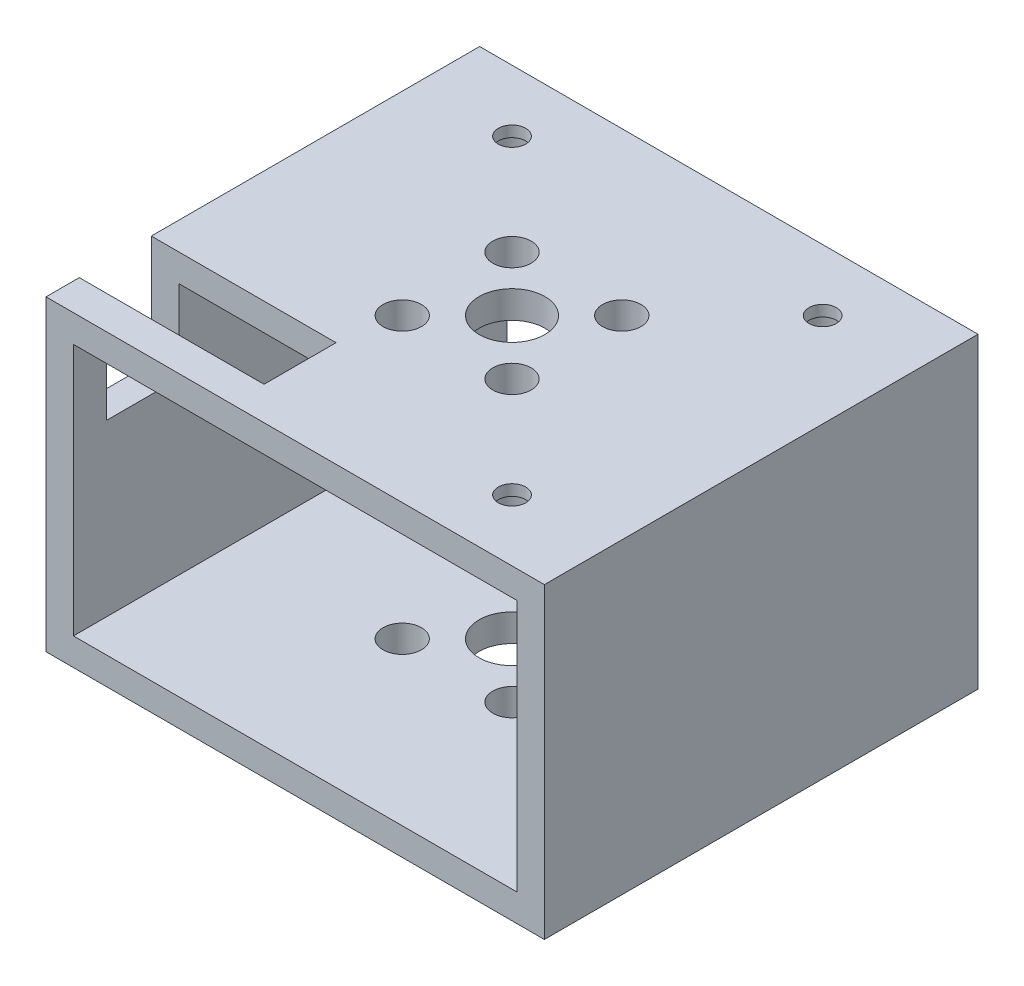
SolidWorks part; units mm, degrees
ref_plane "前视基准面" through (0, 0, 0) normal (0, 0, 1) x (1, 0, 0)
ref_plane "上视基准面" through (0, 0, 0) normal (0, 1, 0) x (1, 0, 0)
ref_plane "右视基准面" through (0, 0, 0) normal (1, 0, 0) x (0, 0, -1)
other "Configuration Table"
sketch "草图1" plane through (0, 0, 0) normal (0, 1, 0) x (1, 0, 0)
  line L0 (-20, 9.75) -> (-25, 9.75) construction
  line L1 (-20, 19.75) -> (20, 19.75) construction
  line L2 (-20, 19.75) -> (-20, -19.75) construction
  line L3 (-20, -19.75) -> (20, -19.75) construction
  line L4 (20, 19.75) -> (20, -19.75) construction
  line L5 (-20, 19.75) -> (20, -19.75) construction
  line L6 (-20, -19.75) -> (20, 19.75) construction
  line L7 (-25, 19.75) -> (25, 19.75)
  line L8 (-25, 19.75) -> (-25, -19.75)
  line L9 (-25, -19.75) -> (25, -19.75)
  line L10 (25, 19.75) -> (25, -19.75)
  line L11 (-25, 19.75) -> (25, -19.75) construction
  line L12 (-25, -19.75) -> (25, 19.75) construction
  line L13 (-27, 19.7501) -> (27, 19.7501)
  line L14 (-27, 19.7501) -> (-27, -19.7501)
  line L15 (-27, -19.7501) -> (27, -19.7501)
  line L16 (27, 19.7501) -> (27, -19.7501)
  line L17 (-27, 19.7501) -> (27, -19.7501) construction
  line L18 (-27, -19.7501) -> (27, 19.7501) construction
  line L19 (0, 19.75) -> (0, 0) construction
  line L20 (0, 0) -> (-20, 0) construction
  circle A0 centre (0, 0) radius 3
  circle A1 centre (-5, 5) radius 1.75
  circle A2 centre (5, 5) radius 1.75
  circle A3 centre (5, -5) radius 1.75
  circle A4 centre (-5, -5) radius 1.75
  circle A5 centre (-22.5, 9.75) radius 1.51
  circle A6 centre (22.5, 9.75) radius 1.51
  circle A7 centre (22.5, -9.75) radius 1.51
  circle A8 centre (-22.5, -9.75) radius 1.51
  point P14 (0, 0)
  dimension "D1" = 6
  dimension "D2" = 3.5
  dimension "D10" = 3.02
  dimension "D3" = 5
  dimension "D4" = 5
  dimension "D6" = 40
  dimension "D7" = 39.5
  dimension "D8" = 5
  dimension "D9" = 2
  dimension "D11" = 10
  dimension "D5" = 4
extrude "凸台-拉伸1" add sketch "草图1" along normal blind 2.5 contours L10 L7 L8 L9 A6 A5 A4 A3 A2 A1 A0 A7 A8
sketch "草图2" plane through (0, 2.5, 0) normal (0, 1, 0) x (1, 0, 0)
  line L0 (-25, 19.75) -> (-25, -19.75) construction
  line L1 (-27, 19.75) -> (-25, 19.75)
  line L2 (-27, 19.75) -> (-27, -19.75)
  line L3 (-27, -19.75) -> (-25, -19.75)
  line L4 (27, 19.75) -> (27, -19.75)
  line L5 (-27, 19.75) -> (27, -19.75) construction
  line L6 (-27, -19.75) -> (27, 19.75) construction
  line L7 (25, 19.75) -> (25, -19.75) construction
  line L8 (25, 19.75) -> (25, -19.75)
  line L9 (-25, 19.75) -> (-25, -19.75)
  line L10 (-25, 19.75) -> (25, 19.75) construction
  line L11 (25, 19.75) -> (27, 19.75)
  line L12 (25, -19.75) -> (27, -19.75)
  point P0 (0, 0)
  dimension "D1" = 2
extrude "凸台-拉伸6" add sketch "草图2" against normal blind 28
sketch "草图3" plane through (0, -25.5, 0) normal (0, -1, 0) x (1, 0, 0)
  line L12 (-25, -19.75) -> (25, -19.75)
  line L13 (25, -19.75) -> (25, 19.75)
  line L14 (25, 19.75) -> (-25, 19.75)
  line L15 (-25, 19.75) -> (-25, -19.75)
  line L16 (-25, -19.75) -> (25, -19.75)
  line L17 (25, -19.75) -> (25, 19.75)
  line L18 (25, 19.75) -> (-25, 19.75)
  line L19 (-25, 19.75) -> (-25, -19.75)
  circle A1 centre (-5, 5) radius 1.75
  circle A2 centre (-5, 5) radius 1.75
  circle A3 centre (5, 5) radius 1.75
  circle A4 centre (5, 5) radius 1.75
  circle A5 centre (5, -5) radius 1.75
  circle A6 centre (5, -5) radius 1.75
  circle A7 centre (-5, -5) radius 1.75
  circle A8 centre (-5, -5) radius 1.75
  circle A9 centre (0, 0) radius 3
  circle A10 centre (0, 0) radius 3
  circle A11 centre (22.5, -9.75) radius 1.51
  circle A12 centre (22.5, -9.75) radius 1.51
  circle A13 centre (-22.5, -9.75) radius 1.51
  circle A14 centre (-22.5, -9.75) radius 1.51
  circle A15 centre (-22.5, 9.75) radius 1.51
  circle A16 centre (-22.5, 9.75) radius 1.51
  circle A17 centre (22.5, 9.75) radius 1.51
  circle A18 centre (22.5, 9.75) radius 1.51
  dimension "D1" = 0
  dimension "D2" = 0
  dimension "D3" = 0
  dimension "D4" = 0
  dimension "D5" = 0
  dimension "D6" = 0
  dimension "D7" = 0
  dimension "D9" = 0
  dimension "D10" = 0
  dimension "D11" = 0
extrude "凸台-拉伸7" add sketch "草图3" against normal blind 2.5
sketch "草图4" plane through (0, -25.5, 0) normal (0, -1, 0) x (1, 0, 0)
  line L1 (-18.8747, -8.4833) -> (-1.933, -8.4833)
  line L2 (-18.8747, -8.4833) -> (-18.8747, -17.7501)
  line L3 (-18.8747, -17.7501) -> (-1.933, -17.7501)
  line L20 (-1.933, -8.4833) -> (-1.933, -17.7501)
extrude "切除-拉伸1" cut sketch "草图4" against normal blind 10
sketch "草图5" plane through (0, -25.5, 0) normal (0, -1, 0) x (1, 0, 0)
  line L0 (0, 19.75) -> (0, -19.75) construction
  line L1 (-27, 19.75) -> (27, 19.75) construction
  line L2 (27, -19.75) -> (-27, -19.75) construction
  line L3 (-20.2, 19.75) -> (-20.2, -19.75) construction
  line L4 (27, -19.75) -> (20.2, -19.75)
  line L5 (-27, 19.75) -> (-20.2, 19.75)
  line L6 (-27, 19.75) -> (-27, -19.75)
  line L7 (-27, -19.75) -> (-20.2, -19.75)
  line L8 (-20.2, 19.75) -> (-20.2, -19.75)
  line L9 (20.2, 19.75) -> (20.2, -19.75)
  line L10 (27, 19.75) -> (20.2, 19.75)
  line L11 (27, 19.75) -> (27, -19.75)
  circle A0 centre (-22.5, 9.75) radius 1.51 construction
  circle A1 centre (-22.5, -9.75) radius 1.51 construction
  dimension "D1" = 20.2
extrude "凸台-拉伸8" add sketch "草图5" against normal blind 29
sketch "草图6" plane through (0, 0, 19.75) normal (0, 0, 1) x (1, 0, 0)
  line L0 (-20.2, 2.5) -> (20.2, 2.5) construction
  line L1 (-22.7, 2.5) -> (22.7, 2.5)
  line L2 (-22.7, 2.5) -> (-22.7, -25.5)
  line L3 (-22.7, -25.5) -> (22.7, -25.5)
  line L4 (22.7, 2.5) -> (22.7, -25.5)
  line L5 (-27, -25.5) -> (27, -25.5) construction
  line L6 (-20.2, 0) -> (-20.2, -23) construction
  line L7 (20.2, 0) -> (20.2, -23) construction
  dimension "D1" = 2.5
  dimension "D2" = 2.5
extrude "切除-拉伸2" cut sketch "草图6" against normal through all flip side to cut
sketch "草图7" plane through (0, 2.5, 0) normal (0, 1, 0) x (1, 0, 0)
  line L1 (-18, 18) -> (18, 18) construction
  line L2 (-18, 18) -> (-18, -18) construction
  line L3 (-18, -18) -> (18, -18) construction
  line L4 (18, 18) -> (18, -18) construction
  line L5 (-18, 18) -> (18, -18) construction
  line L6 (-18, -18) -> (18, 18) construction
  circle A0 centre (14.15, 14.15) radius 1.25
  circle A1 centre (14.15, -14.15) radius 1.25
  circle A2 centre (-14.15, -14.15) radius 1.25
  circle A3 centre (-14.15, 14.15) radius 1.25
  point P0 (0, 0)
  point P17 (0, 0)
  dimension "D3" = 3.85
  dimension "D6" = 2.5
  dimension "D1" = 36
  dimension "D2" = 36
  dimension "D4" = 3.85
  dimension "D5" = 4
extrude "切除-拉伸3" cut sketch "草图7" against normal blind 10
sketch "草图8" plane through (0, 0, 0) normal (0, -1, 0) x (1, 0, 0)
  circle A0 centre (-14.15, -14.15) radius 2
  circle A1 centre (-14.15, 14.15) radius 2
  circle A2 centre (14.15, 14.15) radius 2
  circle A3 centre (14.15, -14.15) radius 2
  point P12 (0, 0)
  dimension "D1" = 4
  dimension "D2" = 4
extrude "切除-拉伸4" cut sketch "草图8" against normal blind 1.5
sketch "草图9" plane through (0, 2.5, 0) normal (0, 1, 0) x (1, 0, 0)
  line L0 (-22.7, 19.75) -> (-22.7, -19.75) construction
  line L1 (-22.7, -10.1571) -> (-5.8721, -10.1571)
  line L2 (-22.7, -10.1571) -> (-22.7, -16.7169)
  line L3 (-22.7, -16.7169) -> (-5.8721, -16.7169)
  line L4 (-5.8721, -10.1571) -> (-5.8721, -16.7169)
extrude "切除-拉伸5" cut sketch "草图9" against normal blind 10
